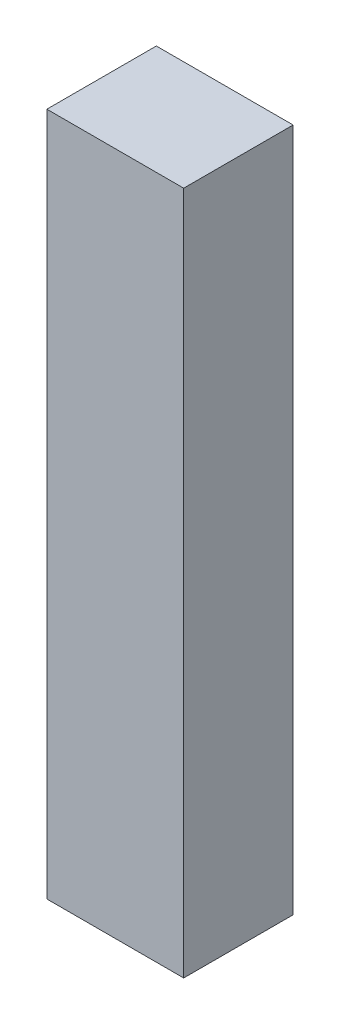
SolidWorks part; units mm, degrees
ref_plane "Front Plane" through (0, 0, 0) normal (1, 0, 0) x (0, 1, 0)
ref_plane "Top Plane" through (0, 0, 0) normal (0, 0, 1) x (0, 1, 0)
ref_plane "Right Plane" through (0, 0, 0) normal (0, 1, 0) x (-1, 0, 0)
sketch "Sketch2" plane through (0, 0, 0) normal (0, 1, 0) x (-1, 0, 0)
  line L1 (-5, -4) -> (5, -4)
  line L2 (-5, -4) -> (-5, 4)
  line L3 (-5, 4) -> (5, 4)
  line L4 (5, -4) -> (5, 4)
  line L5 (-5, -4) -> (5, 4) construction
  line L6 (-5, 4) -> (5, -4) construction
  point P0 (0, 0)
  dimension "D1" = 10
  dimension "D2" = 8
extrude "Boss-Extrude1" add sketch "Sketch2" along normal mid plane 50
